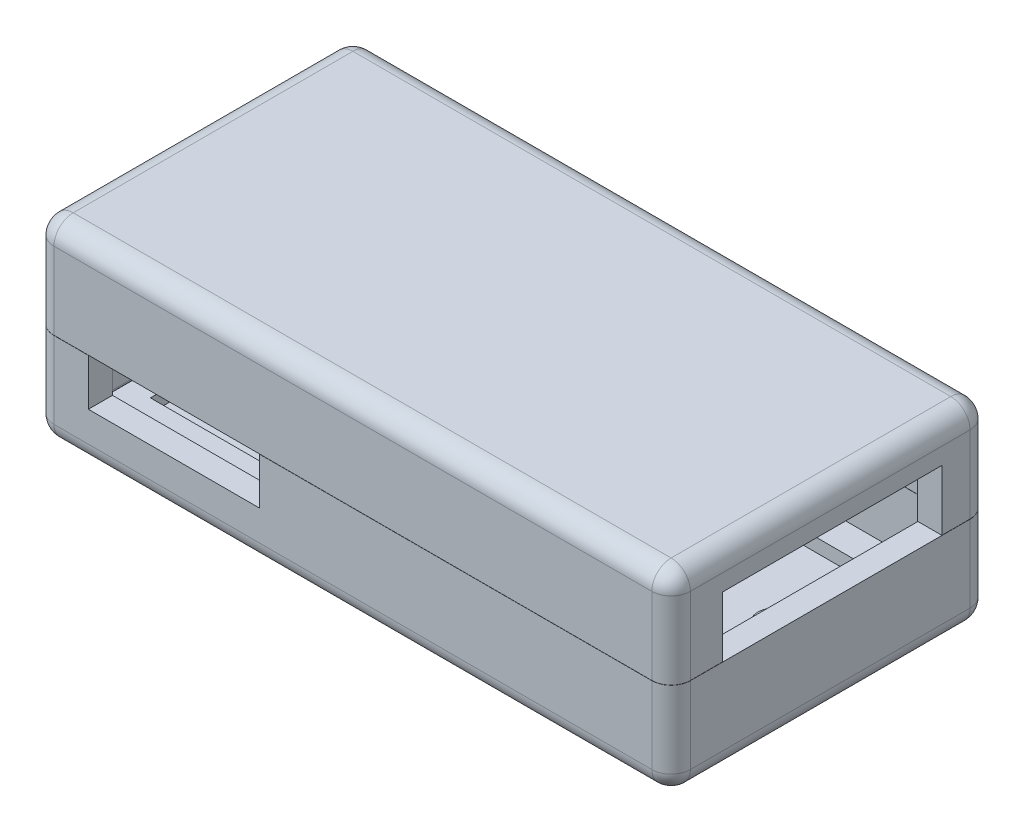
SolidWorks part; units mm, degrees
ref_plane "Front Plane" through (0, 0, 0) normal (0, 0, 1) x (1, 0, 0)
ref_plane "Top Plane" through (0, 0, 0) normal (0, 1, 0) x (1, 0, 0)
ref_plane "Right Plane" through (0, 0, 0) normal (1, 0, 0) x (0, 0, -1)
sketch "Sketch1" plane through (0, 0, 0) normal (0, 1, 0) x (1, 0, 0)
  line L1 (-41.91, -20.955) -> (41.91, -20.955)
  line L2 (-41.91, -20.955) -> (-41.91, 20.955)
  line L3 (-41.91, 20.955) -> (41.91, 20.955)
  line L4 (41.91, -20.955) -> (41.91, 20.955)
  line L5 (-41.91, -20.955) -> (41.91, 20.955) construction
  line L6 (-41.91, 20.955) -> (41.91, -20.955) construction
  point P0 (0, 0)
  dimension "D1" = 83.82
  dimension "D2" = 41.91
extrude "Boss-Extrude1" add sketch "Sketch1" along normal blind 25.4 contours L2 L3 L4 L1
sketch "Sketch2" plane through (0, 0, 20.955) normal (0, 0, 1) x (1, 0, 0)
  line L0 (-41.91, 25.4) -> (-41.91, 0) construction
  line L1 (-34.8361, 6.5253) -> (-12.2682, 6.5253)
  line L2 (-34.8361, 6.5253) -> (-34.8361, 12.6746)
  line L3 (-34.8361, 12.6746) -> (-12.2682, 12.6746)
  line L4 (-12.2682, 6.5253) -> (-12.2682, 12.6746)
  line L5 (-41.91, 0) -> (41.91, 0) construction
  dimension "D1" = 7.0739
  dimension "D2" = 29.6418
  dimension "D3" = 6.5253
  dimension "D4" = 12.6746
extrude "Cut-Extrude1" cut sketch "Sketch2" against normal through all
shell "Shell1" thickness 3.175
sketch "Sketch4" plane through (-41.91, 0, 0) normal (-1, 0, 0) x (0, 0, 1)
  line L1 (-3.683, 6.5253) -> (3.683, 6.5253)
  line L2 (-3.683, 6.5253) -> (-3.683, 12.6746)
  line L3 (-3.683, 12.6746) -> (3.683, 12.6746)
  line L4 (3.683, 6.5253) -> (3.683, 12.6746)
  line L8 (-20.955, 25.4) -> (-20.955, 0) construction
  point P4 (0, 6.5253)
  point P5 (0, 0)
  dimension "D1" = 17.272
extrude "Cut-Extrude3" cut sketch "Sketch4" against normal up to next contours L2 L3 L4 L1
fillet "Fillet1" radius 2.54 12 edges at (-41.91, 12.7, 20.955) (41.91, 12.7, 20.955) (41.91, 12.7, -20.955) (-41.91, 12.7, -20.955) (41.91, 0, 0) (0, 0, -20.955) (-41.91, 0, 0) (0, 0, 20.955) (-41.91, 25.4, 0) (0, 25.4, -20.955) (41.91, 25.4, 0) (0, 25.4, 20.955)
sketch "Sketch5" plane through (0, 0, 20.955) normal (0, 0, 1) x (1, 0, 0)
  line L0 (-12.2682, 12.6746) -> (-34.8361, 12.6746) construction
  line L1 (-44.3024, 12.6746) -> (44.7358, 12.6746)
  line L2 (-44.3024, 12.6746) -> (-44.3024, 12.7)
  line L3 (-44.3024, 12.7) -> (44.7358, 12.7)
  line L4 (44.7358, 12.6746) -> (44.7358, 12.7)
  dimension "D1" = 0.0254
extrude "Cut-Extrude4" cut sketch "Sketch5" against normal through all
sketch "Sketch6" plane through (0, 3.175, 0) normal (0, 1, 0) x (1, 0, 0)
  line L0 (-38.735, 17.78) -> (38.735, 17.78)
  line L1 (38.735, 17.78) -> (38.735, -17.78)
  line L2 (38.735, -17.78) -> (-38.735, -17.78)
  line L3 (-38.735, -17.78) -> (-38.735, 17.78)
  line L4 (-33.655, -13.97) -> (-33.655, 13.97)
  line L5 (-33.655, 13.97) -> (34.925, 13.97)
  line L6 (34.925, 13.97) -> (34.925, 6.35)
  line L7 (34.925, -13.97) -> (-33.655, -13.97)
  line L8 (34.925, -6.35) -> (34.925, -13.97)
  line L9 (34.925, 6.35) -> (31.369, 6.35)
  line L11 (34.925, -6.35) -> (31.369, -6.35)
  line L12 (31.369, 6.35) -> (31.369, -6.35)
  point P16 (31.369, 0)
  point P19 (38.735, 0)
  dimension "D1" = 3.81
  dimension "D2" = 5.08
  dimension "D3" = 3.81
  dimension "D4" = 3.81
  dimension "D5" = 7.366
  dimension "D6" = 12.7
extrude "Boss-Extrude2" add sketch "Sketch6" along normal blind 1.7501
sketch "Sketch7" plane through (0, 4.9251, 0) normal (0, 1, 0) x (1, 0, 0)
  line L0 (31.369, -6.35) -> (31.369, 6.35) construction
  line L2 (38.735, -17.78) -> (38.735, 17.78) construction
  circle A0 centre (34.925, 0) radius 2.54
  circle A1 centre (34.925, 0) radius 0.635
  point P6 (31.369, 0)
  dimension "D1" = 5.08
  dimension "D3" = 1.27
  dimension "D2" = 3.81
extrude "Boss-Extrude3" add sketch "Sketch7" along normal blind 1.6002
sketch "Sketch8" plane through (-38.735, 0, 0) normal (1, 0, 0) x (0, 0, -1)
  line L0 (-17.78, 12.6746) -> (-17.78, 4.9251) construction
  line L1 (-17.78, 6.5253) -> (-3.683, 6.5253)
  line L2 (-17.78, 6.5253) -> (-17.78, 9.7003)
  line L3 (-17.78, 9.7003) -> (-3.683, 9.7003)
  line L4 (-3.683, 6.5253) -> (-3.683, 9.7003)
  line L5 (-3.683, 12.6746) -> (-3.683, 6.5253) construction
  line L6 (3.683, 12.6746) -> (3.683, 6.5253) construction
  line L7 (3.683, 9.7003) -> (17.78, 9.7003)
  line L8 (3.683, 9.7003) -> (3.683, 6.5253)
  line L9 (3.683, 6.5253) -> (17.78, 6.5253)
  line L10 (17.78, 9.7003) -> (17.78, 6.5253)
  line L11 (17.78, 12.6746) -> (17.78, 4.9251) construction
  line L12 (-3.683, 6.5253) -> (3.683, 6.5253) construction
  point P16 (3.683, 6.5253)
  point P19 (-3.683, 6.5253)
  point P20 (-17.78, 7.0462)
  point P21 (-3.683, 6.5253)
  dimension "D1" = 3.175
extrude "Boss-Extrude4" add sketch "Sketch8" along normal blind 3.81
fillet "Fillet2" radius 0.508 2 edges at (-34.925, 6.5253, -10.7315) (-34.925, 6.5253, 10.7315)
sketch "Sketch9" plane through (41.91, 0, 0) normal (1, 0, 0) x (0, 0, -1)
  line L0 (-18.415, 12.7) -> (18.415, 12.7) construction
  line L1 (-14.175, 12.7) -> (14.6952, 12.7)
  line L2 (-14.175, 12.7) -> (-14.175, 20.6689)
  line L3 (-14.175, 20.6689) -> (14.6952, 20.6689)
  line L4 (14.6952, 12.7) -> (14.6952, 20.6689)
extrude "Cut-Extrude5" cut sketch "Sketch9" against normal up to next (3.175 mm away)
equation "\"wallThickness\"= 1 / 8in"
equation "\"D1@Sketch1\"=3.05in+2*\"wallThickness\""
equation "\"D2@Sketch1\"=1.4in+2*\"wallThickness\""
equation "\"D1@Sketch2\"=.1535+\"wallThickness\""
equation "\"D2@Sketch2\"=1.042+\"wallThickness\""
equation "\"D3@Sketch2\"=.1319+\"wallThickness\""
equation "\"D4@Sketch2\"=.374+\"wallThickness\""
equation "\"D1@Sketch4\"=0.555in+\"wallThickness\""
equation "\"D1@Shell1\"= \"wallThickness\""
equation "\"D1@Sketch8\"=\"wallThickness\""
